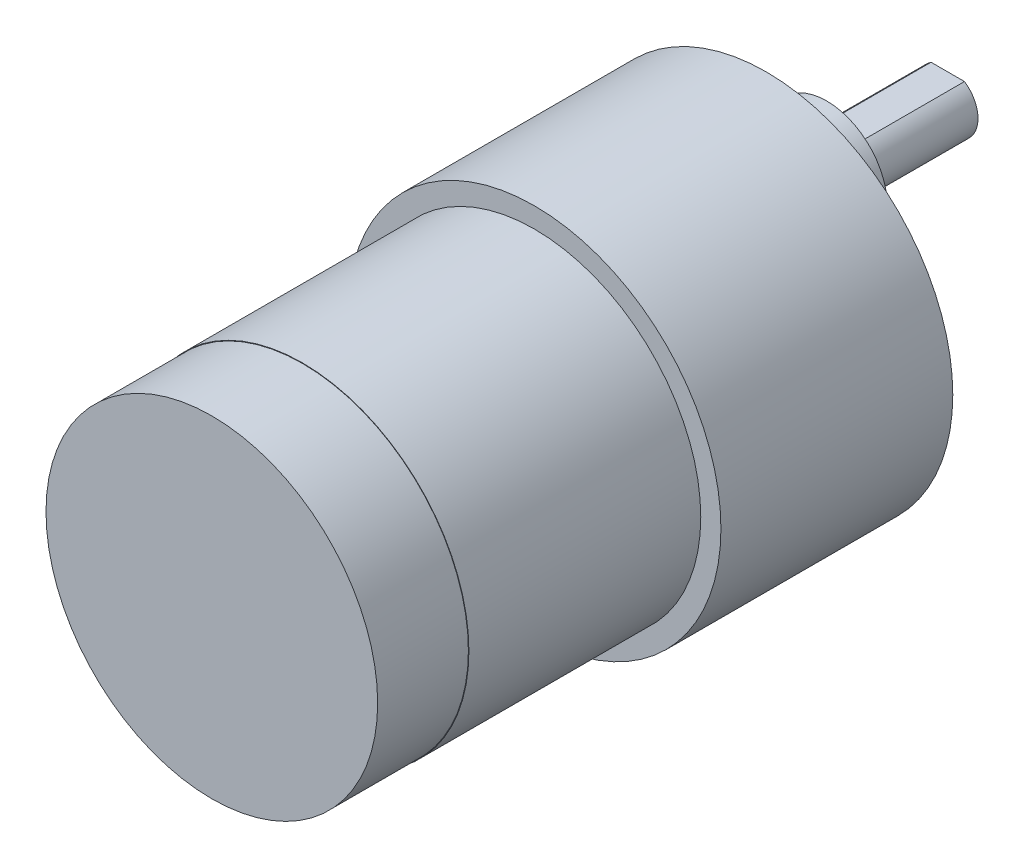
SolidWorks part; units mm, degrees
material "6061 Alloy"
ref_plane "前视基准面" through (0, 0, 0) normal (0, 0, 1) x (1, 0, 0)
ref_plane "上视基准面" through (0, 0, 0) normal (0, 1, 0) x (1, 0, 0)
ref_plane "右视基准面" through (0, 0, 0) normal (1, 0, 0) x (0, 0, -1)
sketch "Sketch1" plane through (0, 0, 0) normal (0, 0, 1) x (1, 0, 0)
  circle A0 centre (0, 0) radius 18.5
  dimension "D1" = 37
extrude "Boss-Extrude1" add sketch "Sketch1" along normal blind 23
sketch "Sketch2" plane through (0, 0, 23) normal (0, 0, 1) x (1, 0, 0)
  circle A0 centre (0, 0) radius 16.5
  dimension "D1" = 33
extrude "Boss-Extrude2" add sketch "Sketch2" along normal blind 23
sketch "Sketch3" plane through (0, 0, 0) normal (0, 0, -1) x (-1, 0, 0)
  circle A0 centre (0, 7) radius 6
  dimension "D2" = 12
  dimension "D1" = 7
extrude "Boss-Extrude3" add sketch "Sketch3" along normal blind 6
sketch "Sketch4" plane through (0, 0, -6) normal (0, 0, -1) x (-1, 0, 0)
  circle A0 centre (0, 7) radius 3
  dimension "D1" = 6
extrude "Boss-Extrude4" add sketch "Sketch4" along normal blind 12
ref_plane "Plane1" through (0, 9.5, 0) normal (0, 1, 0) x (1, 0, 0)
sketch "Sketch5" plane through (0, 9.5, 0) normal (0, 1, 0) x (1, 0, 0)
  line L0 (3, 6) -> (3, 18) construction
  line L1 (-3, 18) -> (3, 18)
  line L2 (-3, 18) -> (-3, 6.5)
  line L3 (-3, 6.5) -> (3, 6.5)
  line L4 (3, 18) -> (3, 6.5)
  line L5 (6, 6) -> (-6, 6) construction
  dimension "D1" = 0.5
extrude "Cut-Extrude1" cut sketch "Sketch5" along normal blind 12
hole_wizard "M3 Tapped Hole1" positions "Sketch7" profile "Sketch8" tap size "M3" standard "GB"
sketch "Sketch7" plane through (0, 0, 0) normal (0, 0, -1) x (-1, 0, 0)
  point P0 (-15.5, 0)
  dimension "D1" = 15.5
sketch "Sketch8" plane through (15.5, 0, 0) normal (1, 0, 0) x (0, 1, 0)
  line L0 (0, 0) -> (0, 5.7511)
  line L1 (0, 5.7511) -> (1.25, 5)
  line L2 (1.25, 5) -> (1.25, 0)
  line L5 (1.25, 0) -> (0, 0)
  line L10 (0, 5.7511) -> (-1.25, 5) construction
  line L11 (0, -6.35) -> (0, 107.95) construction
  dimension "Tap Drill Dia." = 2.5
  dimension "Tap Drill Depth" = 5
  dimension "Drill Angle" = 118
cosmetic thread "Hole Thread1" parameters "D1"=4.5, "D2"=3
pattern_circular "CirPattern1" count 6 over 360 about axis through (0, 0, 0) along (0, 0, 1) of "M3 Tapped Hole1"
sketch "Sketch9" plane through (0, 0, 46) normal (0, 0, 1) x (1, 0, 0)
  circle A0 centre (0, 0) radius 16.45
  dimension "D1" = 32.9
extrude "Boss-Extrude5" add sketch "Sketch9" along normal blind 9
